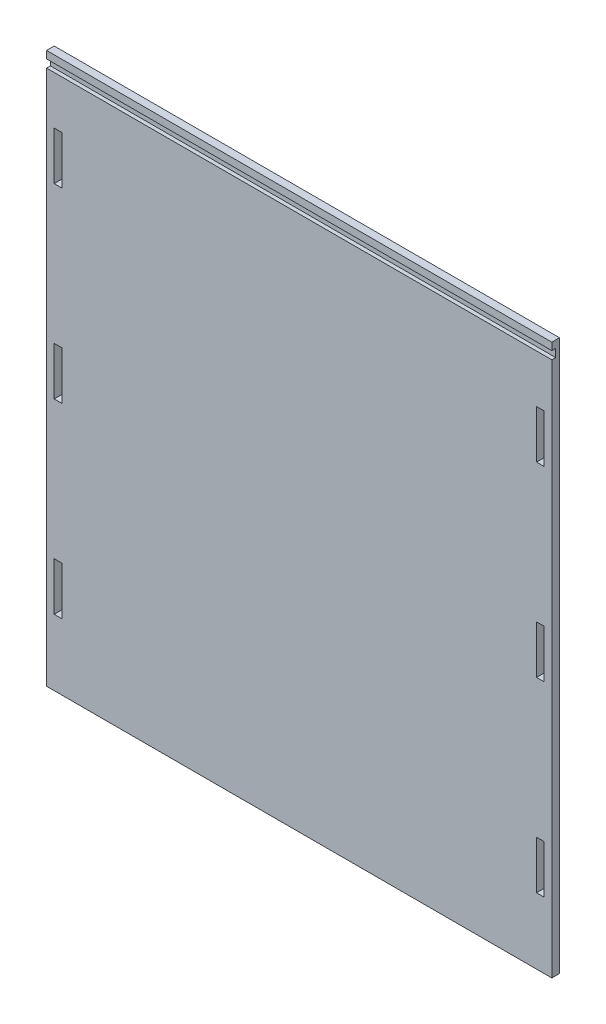
SolidWorks part; units mm, degrees
ref_plane "Front Plane" through (0, 0, 0) normal (0, 0, 1) x (1, 0, 0)
ref_plane "Top Plane" through (0, 0, 0) normal (0, 1, 0) x (1, 0, 0)
ref_plane "Right Plane" through (0, 0, 0) normal (1, 0, 0) x (0, 0, -1)
sketch "Sketch1" plane through (0, 0, 0) normal (0, 0, 1) x (1, 0, 0)
  line L0 (6.35, 405) -> (6.35, 365)
  line L1 (0, 0) -> (420, 0)
  line L2 (0, 0) -> (0, 457.7)
  line L3 (0, 457.7) -> (6.35, 457.7)
  line L4 (420, 0) -> (420, 457.7)
  line L6 (12.7, 365) -> (12.7, 405)
  line L10 (12.7, 457.7) -> (407.3, 457.7)
  line L11 (413.65, 457.7) -> (420, 457.7)
  line L12 (407.3, 457.7) -> (413.65, 457.7)
  line L17 (407.3, 405) -> (413.65, 405)
  line L18 (413.65, 405) -> (413.65, 365)
  line L19 (413.65, 365) -> (407.3, 365)
  line L20 (407.3, 365) -> (407.3, 405)
  line L21 (6.35, 405) -> (12.7, 405)
  line L22 (6.35, 365) -> (12.7, 365)
  line L23 (6.35, 457.7) -> (12.7, 457.7)
  line L24 (12.7, 250) -> (12.7, 210)
  line L25 (12.7, 210) -> (6.35, 210)
  line L26 (6.35, 210) -> (6.35, 250)
  line L27 (6.35, 250) -> (12.7, 250)
  line L28 (413.65, 250) -> (413.65, 210)
  line L29 (413.65, 210) -> (407.3, 210)
  line L30 (407.3, 210) -> (407.3, 250)
  line L31 (407.3, 250) -> (413.65, 250)
  line L32 (413.65, 95) -> (413.65, 55)
  line L33 (413.65, 55) -> (407.3, 55)
  line L34 (407.3, 55) -> (407.3, 95)
  line L35 (407.3, 95) -> (413.65, 95)
  line L36 (12.7, 95) -> (12.7, 55)
  line L37 (12.7, 55) -> (6.35, 55)
  line L38 (6.35, 55) -> (6.35, 95)
  line L39 (6.35, 95) -> (12.7, 95)
  point P6 (9.525, 405)
  dimension "D1" = 457.7
  dimension "D2" = 420
  dimension "D3" = 40
  dimension "D4" = 52.7
  dimension "D5" = 6.35
  dimension "D6" = 6.35
  dimension "D7" = 52.7
  dimension "D8" = 55
  dimension "D9" = 250
  dimension "D10" = 250
  dimension "D12" = 55
extrude "Boss-Extrude1" add sketch "Sketch1" along normal blind 6.35
sketch "Sketch2" plane through (420, 0, 0) normal (1, 0, 0) x (0, 0, -1)
  line L0 (-6.35, 0) -> (-6.35, 457.7) construction
  line L1 (-6.35, 451.604) -> (-3.175, 451.604)
  line L2 (-6.35, 451.604) -> (-6.35, 445)
  line L3 (-6.35, 445) -> (-3.175, 445)
  line L4 (-3.175, 451.604) -> (-3.175, 445)
  line L5 (-6.35, 457.7) -> (0, 457.7) construction
  dimension "D1" = 6.604
  dimension "D2" = 6.096
  dimension "D3" = 3.175
extrude "Cut-Extrude1" cut sketch "Sketch2" against normal through all
